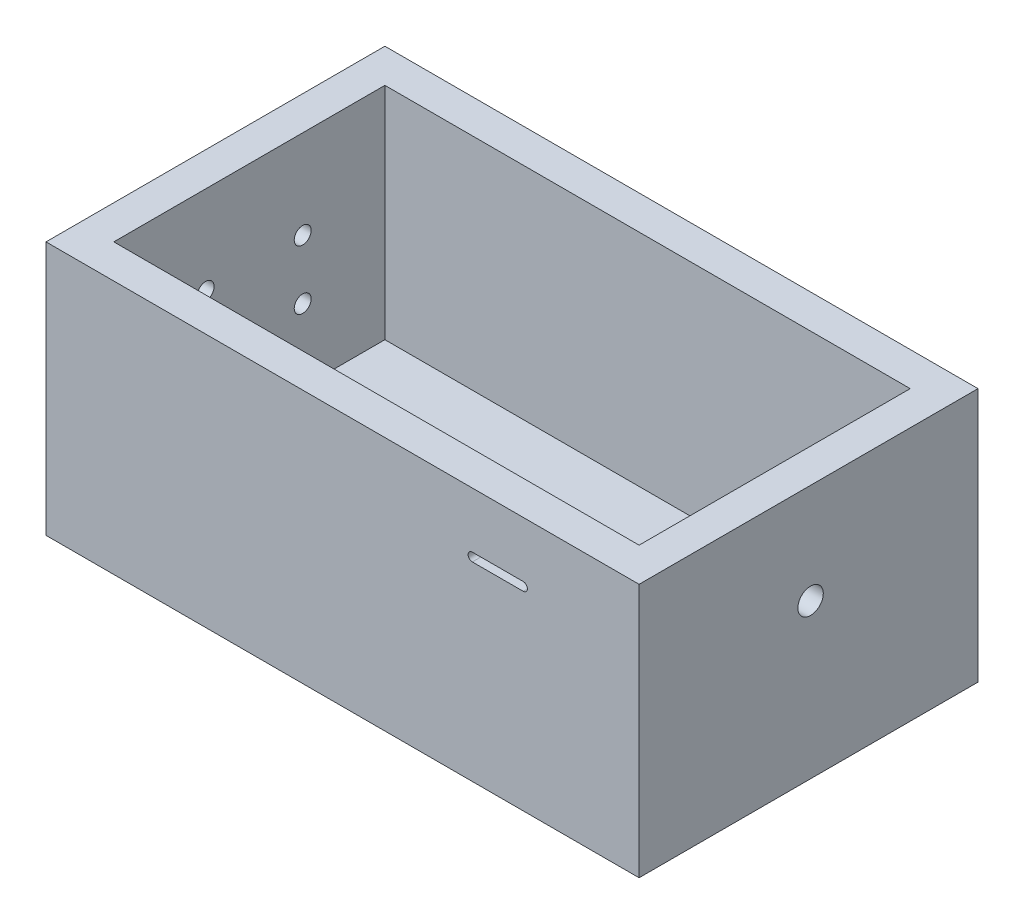
SolidWorks part; units mm, degrees
material "3.0515 (EN-AW 3103)"
ref_plane "前视" through (0, 0, 0) normal (0, 0, 1) x (1, 0, 0)
ref_plane "上视" through (0, 0, 0) normal (0, 1, 0) x (1, 0, 0)
ref_plane "右视" through (0, 0, 0) normal (1, 0, 0) x (0, 0, -1)
sketch "草图2" plane through (0, 0, 0) normal (0, 1, 0) x (1, 0, 0)
  line L1 (-9.2337, 13.4811) -> (340.7663, 13.4811)
  line L2 (-9.2337, 13.4811) -> (-9.2337, -186.5189)
  line L3 (-9.2337, -186.5189) -> (340.7663, -186.5189)
  line L4 (340.7663, 13.4811) -> (340.7663, -186.5189)
  dimension "D1" = 350
  dimension "D2" = 200
extrude "凸台-拉伸1" add sketch "草图2" along normal blind 150 contours L1 L4 L3 L2
shell "抽壳1" thickness 20
sketch "草图3" plane through (-9.2337, 0, 0) normal (-1, 0, 0) x (0, 0, 1)
  circle A0 centre (55.0397, 97.6672) radius 5
  circle A1 centre (112.3143, 97.6672) radius 5
  circle A2 centre (55.0397, 62.6903) radius 5
  circle A3 centre (112.3143, 62.6903) radius 5
  dimension "D1" = 10
  dimension "D2" = 10
  dimension "D3" = 10
  dimension "D4" = 10
extrude "切除-拉伸1" cut sketch "草图3" against normal up to next
sketch "草图4" plane through (340.7663, 0, 0) normal (1, 0, 0) x (0, 0, -1)
  circle A0 centre (-85.3189, 90.9816) radius 7.5
  dimension "D1" = 15
extrude "切除-拉伸2" cut sketch "草图4" against normal up to next
sketch "草图5" plane through (0, 0, 186.5189) normal (0, 0, 1) x (1, 0, 0)
  line L1 (242.3647, 117.2338) -> (272.3647, 117.2338)
  line L3 (242.3647, 112.2338) -> (272.3647, 112.2338)
  arc A0 (242.3647, 117.2338) -> (242.3647, 112.2338) centre (242.3647, 114.7338) ccw
  arc A1 (272.3647, 117.2338) -> (272.3647, 112.2338) centre (272.3647, 114.7338) cw
  dimension "D1" = 30
  dimension "D2" = 5
extrude "切除-拉伸3" cut sketch "草图5" against normal up to next
